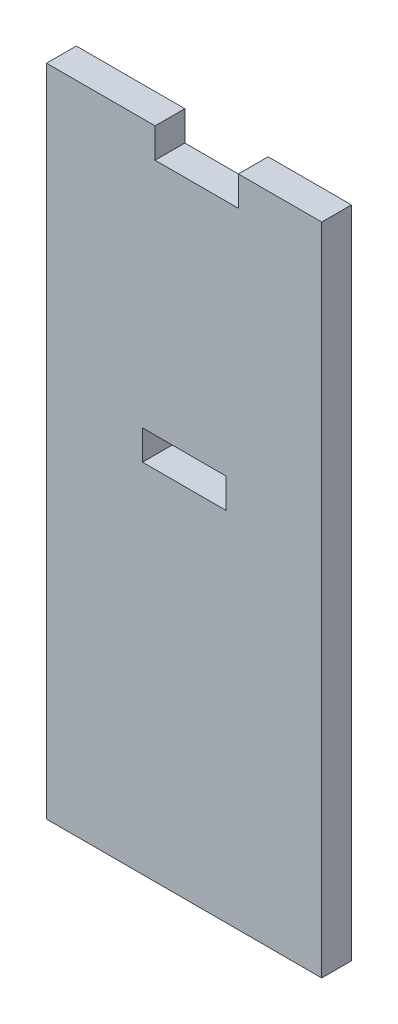
SolidWorks part; units mm, degrees
material "Beech"
ref_plane "Front" through (0, 0, 0) normal (0, 0, 1) x (1, 0, 0)
ref_plane "Top" through (0, 0, 0) normal (0, 1, 0) x (1, 0, 0)
ref_plane "Right" through (0, 0, 0) normal (1, 0, 0) x (0, 0, -1)
sketch "Sketch1" plane through (0, 0, 0) normal (0, 0, 1) x (1, 0, 0)
  line L1 (-11.56, -30) -> (11.56, -30) construction
  line L2 (-11.56, -30) -> (-11.56, 30) construction
  line L3 (-11.56, 30) -> (11.56, 30) construction
  line L4 (11.56, -30) -> (11.56, 30) construction
  line L5 (-11.56, -30) -> (11.56, 30) construction
  line L6 (-11.56, 30) -> (11.56, -30) construction
  line L7 (-3.5, 5) -> (3.5, 5)
  line L8 (-3.5, 5) -> (-3.5, 7.5)
  line L9 (-3.5, 7.5) -> (3.5, 7.5)
  line L10 (3.5, 5) -> (3.5, 7.5)
  line L11 (-3.5, 5) -> (3.5, 7.5) construction
  line L12 (-3.5, 7.5) -> (3.5, 5) construction
  line L16 (11.56, -30) -> (-11.56, -30) construction
  line L17 (11.56, 30) -> (4.56, 30)
  line L18 (4.56, 30) -> (4.56, 27.5)
  line L19 (4.56, 27.5) -> (-2.44, 27.5)
  line L20 (-2.44, 27.5) -> (-2.44, 30)
  line L21 (-2.44, 30) -> (-11.56, 30)
  line L22 (-11.56, 30) -> (-11.56, -25)
  line L23 (-11.56, -25) -> (11.56, -25)
  line L24 (11.56, -25) -> (11.56, 30)
  point P0 (0, 0)
  point P6 (0, 6.25)
  dimension "D1" = 60
  dimension "D2" = 23.12
  dimension "D3" = 7
  dimension "D4" = 2.5
  dimension "D5" = 36.25
  dimension "D6" = 5
extrude "Boss-Extrude1" add sketch "Sketch1" along normal blind 2.5
